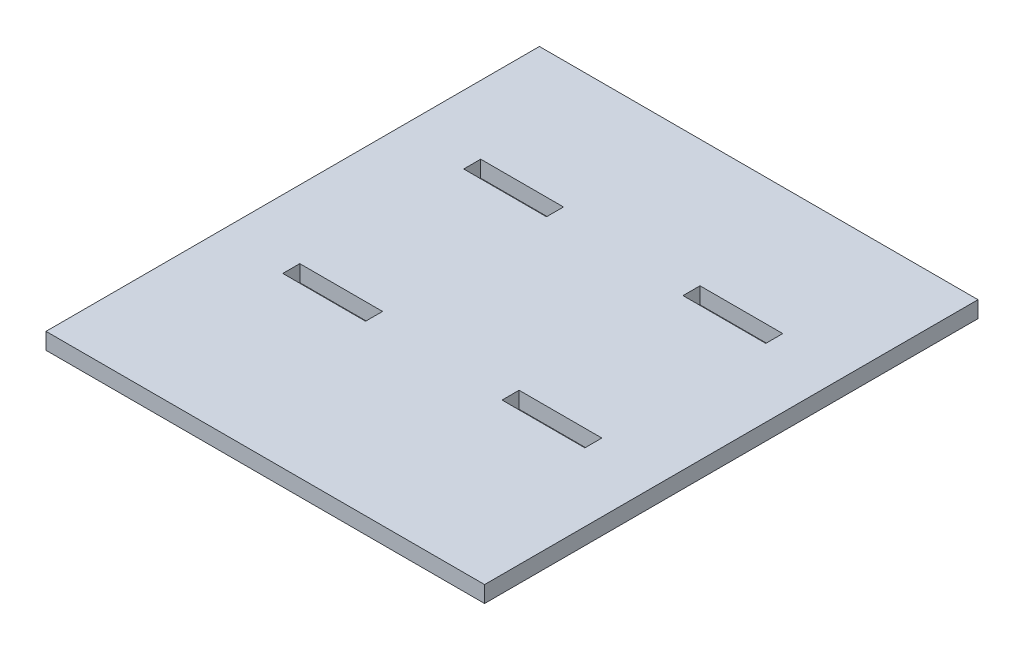
SolidWorks part; units mm, degrees
ref_plane "Front Plane" through (0, 0, 0) normal (0, 0, 1) x (1, 0, 0)
ref_plane "Top Plane" through (0, 0, 0) normal (0, 1, 0) x (1, 0, 0)
ref_plane "Right Plane" through (0, 0, 0) normal (1, 0, 0) x (0, 0, -1)
sketch "Sketch2" plane through (0, 0, 0) normal (0, 1, 0) x (1, 0, 0)
  line L0 (0, 45) -> (80, 45) construction
  line L29 (0, 0) -> (80, 0)
  line L30 (0, 0) -> (0, 90)
  line L47 (0, 90) -> (80, 90)
  line L65 (80, 0) -> (80, 90)
  line L66 (12.45, 33.84) -> (27.55, 33.84)
  line L67 (12.45, 33.84) -> (12.45, 30.74)
  line L68 (12.45, 30.74) -> (27.55, 30.74)
  line L69 (27.55, 33.84) -> (27.55, 30.74)
  line L74 (40, 90) -> (40, 0) construction
  line L75 (12.45, 66.84) -> (27.55, 66.84)
  line L76 (12.45, 66.84) -> (12.45, 63.74)
  line L77 (12.45, 63.74) -> (27.55, 63.74)
  line L78 (27.55, 66.84) -> (27.55, 63.74)
  line L79 (67.55, 30.74) -> (52.45, 30.74)
  line L80 (52.45, 33.84) -> (52.45, 30.74)
  line L81 (67.55, 33.84) -> (52.45, 33.84)
  line L82 (67.55, 33.84) -> (67.55, 30.74)
  line L83 (67.55, 63.74) -> (52.45, 63.74)
  line L84 (52.45, 66.84) -> (52.45, 63.74)
  line L85 (67.55, 66.84) -> (52.45, 66.84)
  line L86 (67.55, 66.84) -> (67.55, 63.74)
  dimension "D1" = 80
  dimension "D2" = 90
  dimension "D3" = 15.1
  dimension "D4" = 3.1
  dimension "D5" = 12.45
  dimension "D6" = 30.74
  dimension "D7" = 15.1
  dimension "D8" = 3.1
  dimension "D9" = 29.9
  dimension "D10" = 12.45
extrude "Boss-Extrude4" add sketch "Sketch2" along normal blind 3
